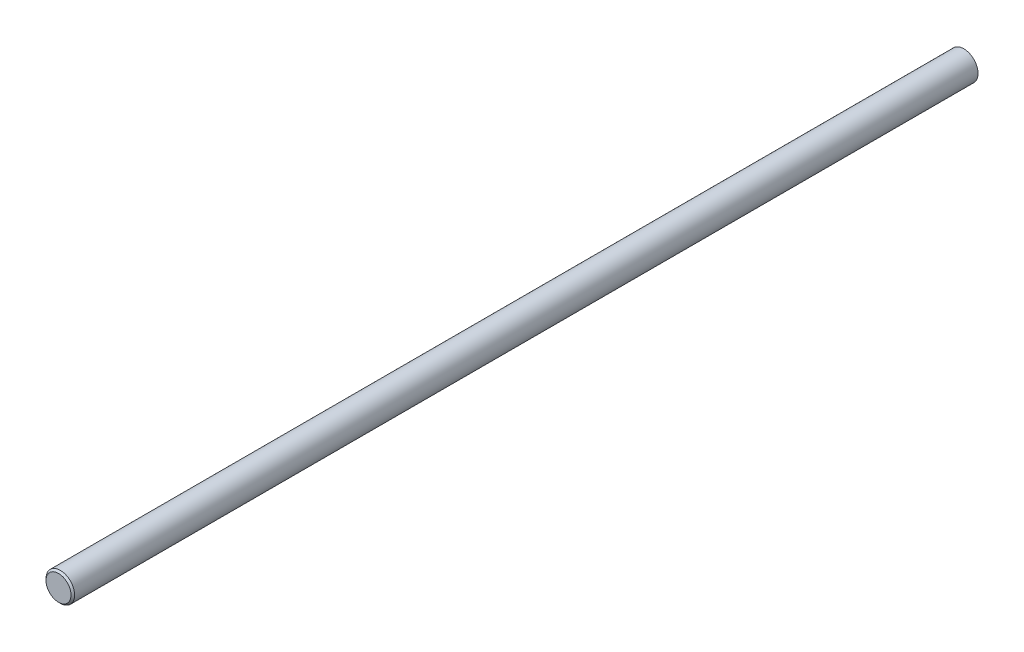
SolidWorks part; units mm, degrees
ref_plane "Front Plane" through (0, 0, 0) normal (0, 0, 1) x (1, 0, 0)
ref_plane "Top Plane" through (0, 0, 0) normal (0, 1, 0) x (1, 0, 0)
ref_plane "Right Plane" through (0, 0, 0) normal (1, 0, 0) x (0, 0, -1)
sketch "Sketch1" plane through (0, 0, 0) normal (0, 0, 1) x (1, 0, 0)
  line L0 (-3, 0) -> (3, 0) construction
  point P4 (0, 0)
  dimension "Diameter" = 6
sketch "Sketch2" plane through (0, 0, 0) normal (1, 0, 0) x (0, 0, -1)
  line L0 (152.4, 0) -> (-152.4, 0) construction
  line L1 (-152.4, 3) -> (-152.4, -3) construction
  line L2 (152.4, 3) -> (152.4, -3) construction
  point P0 (-145.5, 0)
  point P4 (0, 0)
  point P6 (145.5, 0)
  point P10 (152.4, 0)
  point P12 (-152.4, 0)
  dimension "Length" = 304.8
  dimension "D1" = 6.9
  dimension "D2" = 6.9
  dimension "D3" = 6
sketch "Sketch3" plane through (0, 0, 0) normal (0, 0, 1) x (1, 0, 0)
  circle A0 centre (0, 0) radius 3
extrude "Boss-Extrude1" add sketch "Sketch3" along normal mid plane 304.8
chamfer "Chamfer1" distance 0.375 angle 45 2 edges at (3, 0, -152.4) (3, 0, 152.4)
ref_plane "Plane1" through (0, 0, -37.6) normal (0, 0, 1) x (1, 0, 0)
sketch "Sketch4" plane through (0, 0, -37.6) normal (0, 0, 1) x (1, 0, 0)
  circle A0 centre (0, 0) radius 3 construction
  circle A1 centre (0, 0) radius 3
extrude "Cut-Extrude1" cut sketch "Sketch4" against normal through all
equation "\"Length@Boss-Extrude1\" = \"Length@Sketch2\""
equation "\"D3@Sketch2\" = \"Diameter@Sketch1\""
equation "\"D1@Sketch2\" = \"Diameter@Sketch1\" * 1.15"
equation "\"D2@Sketch2\"=\"D1@Sketch2\""
equation "\"D1@Chamfer1\"=.0625*\"Diameter@Sketch1\""
